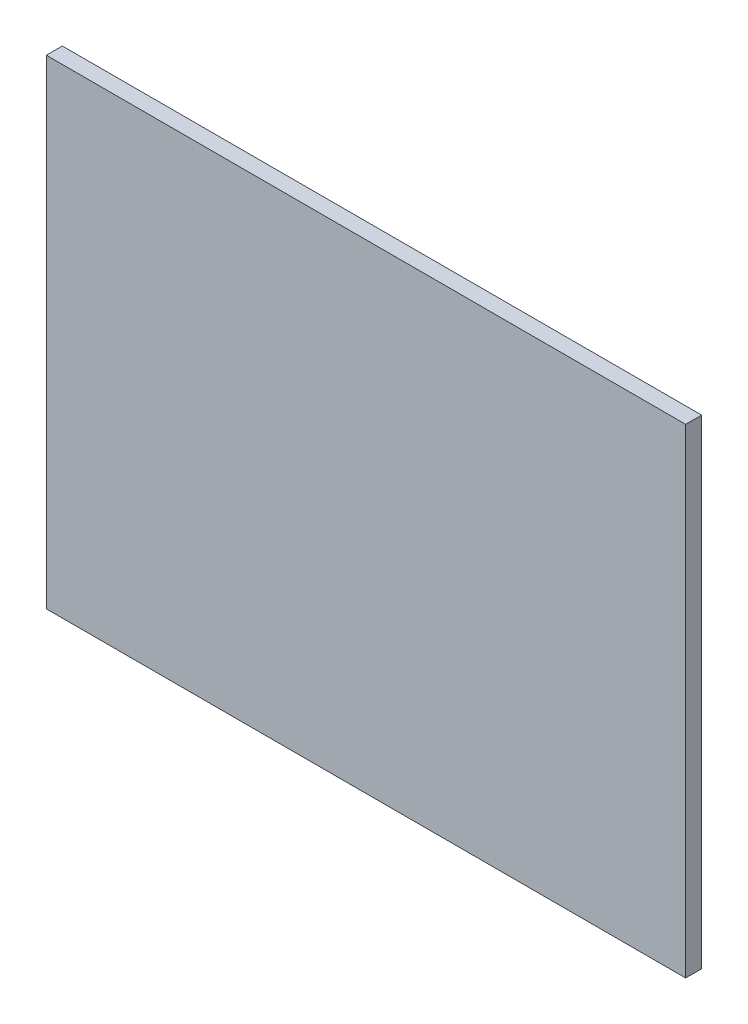
SolidWorks part; units mm, degrees
ref_plane "Front Plane" through (0, 0, 0) normal (0, 0, 1) x (1, 0, 0)
ref_plane "Top Plane" through (0, 0, 0) normal (0, 1, 0) x (1, 0, 0)
ref_plane "Right Plane" through (0, 0, 0) normal (1, 0, 0) x (0, 0, -1)
sketch "Çizim1" plane through (0, 0, 0) normal (0, 0, 1) x (1, 0, 0)
  line L0 (0, 75) -> (0, -75) construction
  line L5 (-100, 75) -> (100, 75)
  line L6 (-100, 75) -> (-100, -75)
  line L7 (-100, -75) -> (100, -75)
  line L8 (100, 75) -> (100, -75)
  line L9 (-100, 0) -> (100, 0) construction
  point P8 (0, 0)
  dimension "D1" = 200
  dimension "D2" = 150
extrude "Yükseklik-Ekstrüzyon1" add sketch "Çizim1" along normal blind 5
